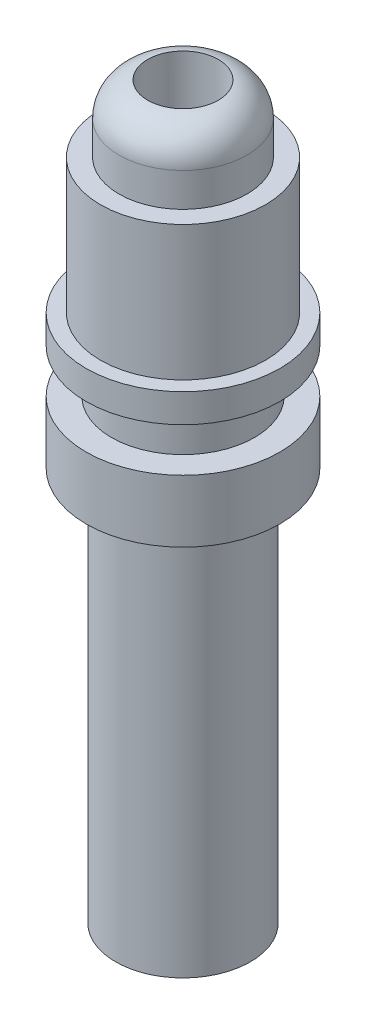
SolidWorks part; units mm, degrees
ref_plane "Front Plane" through (0, 0, 0) normal (0, 0, 1) x (1, 0, 0)
ref_plane "Top Plane" through (0, 0, 0) normal (0, 1, 0) x (1, 0, 0)
ref_plane "Right Plane" through (0, 0, 0) normal (1, 0, 0) x (0, 0, -1)
sketch "Sketch1" plane through (0, 0, 0) normal (0, 1, 0) x (1, 0, 0)
  circle A0 centre (0, 0) radius 5.75
  dimension "D1" = 11.5
extrude "Boss-Extrude1" add sketch "Sketch1" along normal blind 16
sketch "Sketch2" plane through (0, 16, 0) normal (0, 1, 0) x (1, 0, 0)
  circle A0 centre (0, 0) radius 4.9
  dimension "D1" = 9.8
extrude "Cut-Extrude1" cut sketch "Sketch2" against normal blind 8 flip side to cut
sketch "Sketch3" plane through (0, 16, 0) normal (0, 1, 0) x (1, 0, 0)
  circle A0 centre (0, 0) radius 3.8
  dimension "D1" = 7.6
extrude "Boss-Extrude2" add sketch "Sketch3" along normal blind 4
fillet "Fillet2" radius 2 1 edges at (0, 20, 3.8)
sketch "Sketch4" plane through (0, 0, 0) normal (0, -1, 0) x (1, 0, 0)
  circle A0 centre (0, 0) radius 4
  dimension "D1" = 8
extrude "Boss-Extrude3" add sketch "Sketch4" along normal blind 23.4
sketch "Sketch5" plane through (0, -23.4, 0) normal (0, -1, 0) x (1, 0, 0)
  circle A0 centre (0, 0) radius 1.25
  dimension "D1" = 2.5
ref_axis "Axis1" through (0, 8, 0) along (0, -1, 0)
sketch "Sketch12" plane through (0, 0, 0) normal (1, 0, 0) x (0, 0, -1)
  line L0 (-5.75, 6.3) -> (-4.25, 6.3)
  line L1 (-5.75, 8) -> (-5.75, 0) construction
  line L2 (-4.25, 6.3) -> (-4.25, 3.7)
  line L3 (-4.25, 3.7) -> (-5.75, 3.7)
  line L4 (-5.75, 8) -> (-5.75, 0) construction
  line L5 (-5.75, 3.7) -> (-5.75, 6.3)
  line L6 (5.75, 8) -> (-5.75, 8) construction
  dimension "D1" = 2.6
  dimension "D2" = 1.7
  dimension "D3" = 1.5
revolve "Cut-Revolve2" cut sketch "Sketch12" angle 360 about axis through (0, 8, 0) along (0, -1, 0)
extrude "Cut-Extrude2" cut sketch "Sketch5" against normal up to next
sketch "Sketch13" plane through (0, 20, 0) normal (0, 1, 0) x (1, 0, 0)
  circle A0 centre (0, 0) radius 2.1
  dimension "D1" = 4.2
extrude "Cut-Extrude3" cut sketch "Sketch13" against normal blind 12
